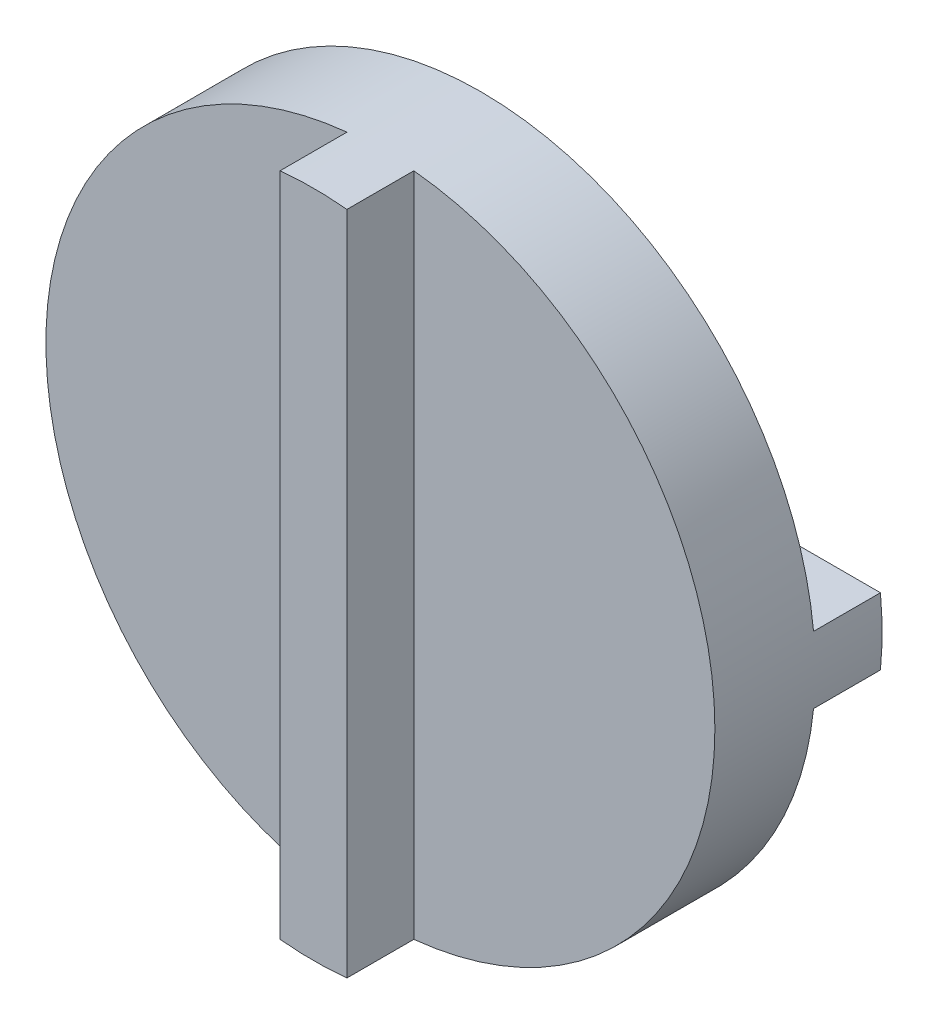
SolidWorks part; units mm, degrees
ref_plane "Front Plane" through (0, 0, 0) normal (0, 0, 1) x (1, 0, 0)
ref_plane "Top Plane" through (0, 0, 0) normal (0, 1, 0) x (1, 0, 0)
ref_plane "Right Plane" through (0, 0, 0) normal (1, 0, 0) x (0, 0, -1)
sketch "Sketch1" plane through (0, 0, 0) normal (0, 0, 1) x (1, 0, 0)
  circle A0 centre (0, 0) radius 50
  point P3 (-11.9444, -10.9746)
  point P4 (0, 0)
  dimension "D1" = 100
extrude "Boss-Extrude1" add sketch "Sketch1" along normal blind 15
sketch "Sketch2" plane through (0, 0, 15) normal (0, 0, 1) x (1, 0, 0)
  line L0 (0, 65.769) -> (0, -65.769) construction
  line L1 (-5, 49.7494) -> (-5, -49.7494)
  line L2 (5, 49.7494) -> (5, -49.7494)
  arc A0 (-5, -49.7494) -> (5, -49.7494) centre (0, 0) ccw
  arc A1 (5, 49.7494) -> (-5, 49.7494) centre (0, 0) ccw
  circle A2 centre (0, 0) radius 50 construction
  point P4 (0, 0)
  point P8 (0, 0)
  point P12 (0, 0)
  dimension "D1" = 10
extrude "Boss-Extrude2" add sketch "Sketch2" along normal blind 10
sketch "Sketch3" plane through (0, 0, 0) normal (0, 0, -1) x (-1, 0, 0)
  line L0 (-50, 0) -> (50, 0) construction
  line L3 (-49.7494, -5) -> (49.7494, -5)
  line L4 (-49.7494, 5) -> (49.7494, 5)
  circle A2 centre (0, 0) radius 50 construction
  arc A3 (49.7494, -5) -> (49.7494, 5) centre (0, 0) ccw
  arc A4 (-49.7494, 5) -> (-49.7494, -5) centre (0, 0) ccw
  point P6 (0, 0)
  dimension "D1" = 10
extrude "Boss-Extrude3" add sketch "Sketch3" along normal blind 10
